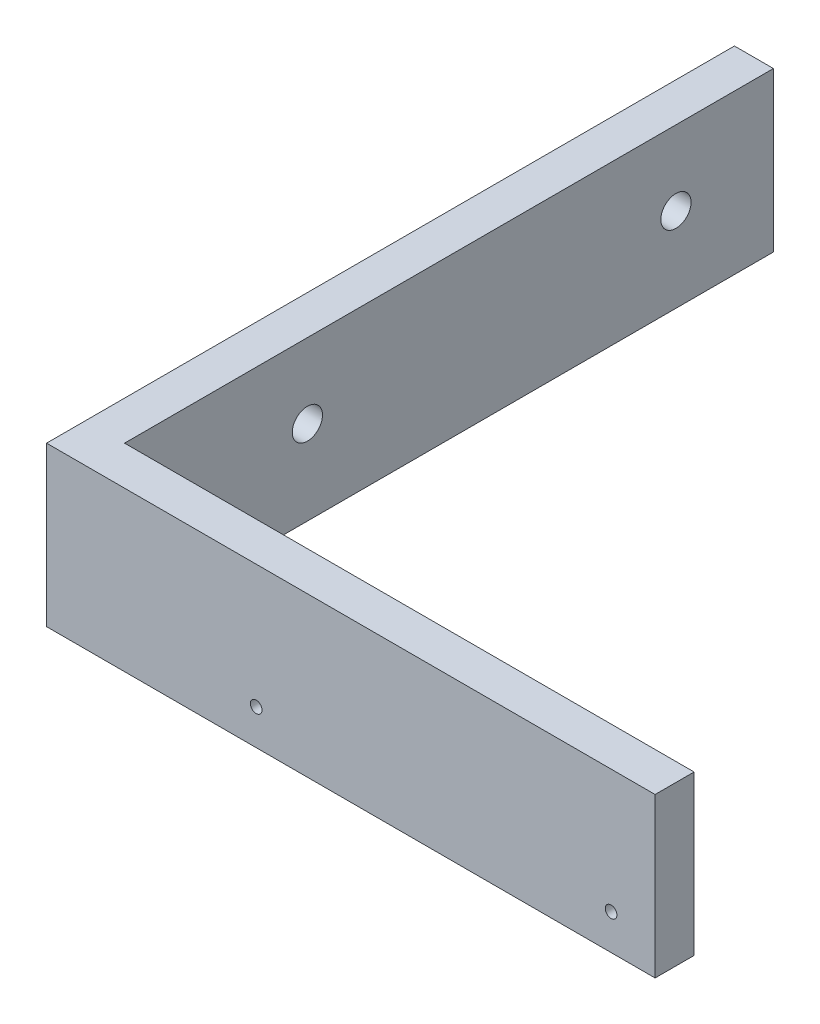
SolidWorks part; units mm, degrees
ref_plane "前视基准面" through (0, 0, 0) normal (0, 0, 1) x (1, 0, 0)
ref_plane "上视基准面" through (0, 0, 0) normal (0, 1, 0) x (1, 0, 0)
ref_plane "右视基准面" through (0, 0, 0) normal (1, 0, 0) x (0, 0, -1)
sketch "草图1" plane through (0, 0, 0) normal (0, 0, 1) x (1, 0, 0)
  line L2 (-29.15, 4.6184) -> (-29.15, -3.6184) construction
  line L3 (-29.15, 8.15) -> (-29.15, -8.15)
  line L4 (27.2634, -8) -> (27.2634, 8)
  line L5 (27.2634, 8) -> (-27.2634, 8)
  line L6 (-27.2634, 8) -> (-27.2634, -8)
  line L7 (-27.2634, -8) -> (27.2634, -8)
  line L8 (27.2634, -8.15) -> (27.2634, 8.15)
  line L21 (-27.2634, 8.15) -> (27.2634, 8.15)
  line L22 (-29.15, 8.15) -> (27.2634, 8.15)
  line L23 (-29.15, 8.15) -> (-35.15, 8.15)
  line L24 (27.2634, -8.15) -> (-27.2634, -8.15)
  line L25 (27.2634, -8.15) -> (-29.15, -8.15)
  line L26 (-29.15, 8.15) -> (-29.15, -8.15)
  line L27 (-29.15, -8.15) -> (-35.15, -8.15)
  line L28 (-35.15, 8.15) -> (-35.15, -8.15)
  dimension "D2" = 6
  dimension "D1" = 0
  dimension "D4" = 0.15
  dimension "D5" = 0.15
extrude "凸台-拉伸1" add sketch "草图1" along normal blind 4
sketch "草图3" plane through (-35.15, 0, 0) normal (-1, 0, 0) x (0, 0, 1)
  line L1 (4, 8.15) -> (-66.55, 8.15)
  line L2 (4, 8.15) -> (4, -8.15)
  line L3 (4, -8.15) -> (-66.55, -8.15)
  line L4 (-66.55, 8.15) -> (-66.55, -8.15)
  circle A0 centre (-56.55, 0.5) radius 1.5 construction
  circle A1 centre (-56.55, 0.5) radius 1.55
  circle A2 centre (-18.75, 0.5) radius 1.55
  dimension "D2" = 3.1
  dimension "D1" = 10
extrude "凸台-拉伸3" add sketch "草图3" against normal blind 4
sketch "草图4" plane through (0, 0, 0) normal (0, 0, -1) x (-1, 0, 0)
  circle A0 centre (-22.75, -4.52) radius 0.6
  circle A1 centre (13.65, -4.52) radius 0.6
  dimension "D1" = 1.2
extrude "切除-拉伸1" cut sketch "草图4" against normal up to next
